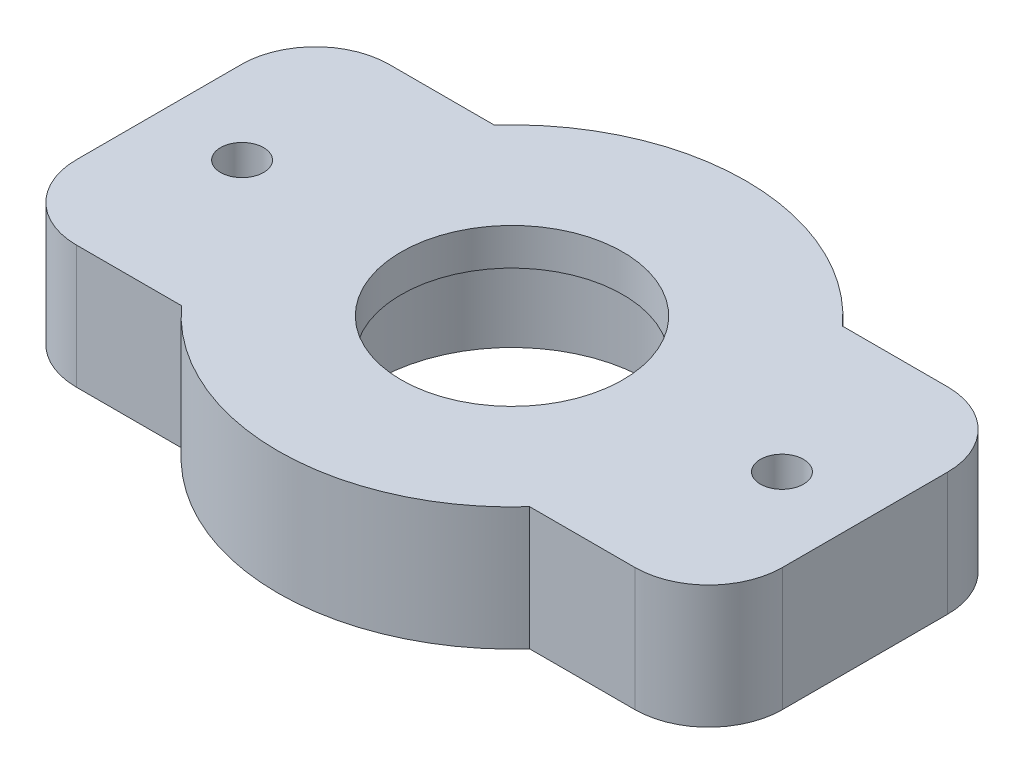
SolidWorks part; units mm, degrees
ref_plane "Front Plane" through (0, 0, 0) normal (0, 0, 1) x (1, 0, 0)
ref_plane "Top Plane" through (0, 0, 0) normal (0, 1, 0) x (1, 0, 0)
ref_plane "Right Plane" through (0, 0, 0) normal (1, 0, 0) x (0, 0, -1)
sketch "Sketch1" plane through (0, 0, 0) normal (0, 1, 0) x (1, 0, 0)
  line L0 (-21.9203, 0) -> (0, 0) construction
  line L1 (28.6703, -12.7) -> (14.1319, -12.7)
  line L2 (28.6703, -12.7) -> (28.6703, 12.7)
  line L3 (28.6703, 12.7) -> (14.1319, 12.7)
  line L4 (-28.6703, -12.7) -> (-28.6703, 12.7)
  line L5 (28.6703, -12.7) -> (-28.6703, 12.7) construction
  line L6 (28.6703, 12.7) -> (-28.6703, -12.7) construction
  line L7 (0, 0) -> (21.9203, 0) construction
  line L8 (-14.1319, -12.7) -> (-28.6703, -12.7)
  line L9 (-14.1319, 12.7) -> (-28.6703, 12.7)
  circle A0 centre (0, 0) radius 11
  arc A1 (-14.1319, -12.7) -> (14.1319, -12.7) centre (0, 0) ccw
  circle A2 centre (21.9203, 0) radius 1.75
  circle A3 centre (-21.9203, 0) radius 1.75
  arc A4 (14.1319, 12.7) -> (-14.1319, 12.7) centre (0, 0) ccw
  dimension "D1" = 22
  dimension "D3" = 3.5
  dimension "D2" = 25.4
  dimension "D4" = 8
  dimension "D5" = 43.8406
  dimension "D6" = 5
extrude "Boss-Extrude1" add sketch "Sketch1" along normal blind 10
sketch "Sketch2" plane through (0, 10, 0) normal (0, 1, 0) x (1, 0, 0)
  circle A0 centre (0, 0) radius 9
  circle A1 centre (0, 0) radius 11 construction
  circle A2 centre (0, 0) radius 11
  dimension "D1" = 2
extrude "Boss-Extrude2" add sketch "Sketch2" against normal blind 3
fillet "Fillet1" radius 6 4 edges at (28.6703, 5, -12.7) (28.6703, 5, 12.7) (-28.6703, 5, 12.7) (-28.6703, 5, -12.7)
equation "\"D5@Sketch1\"=sqr(2)*31"
